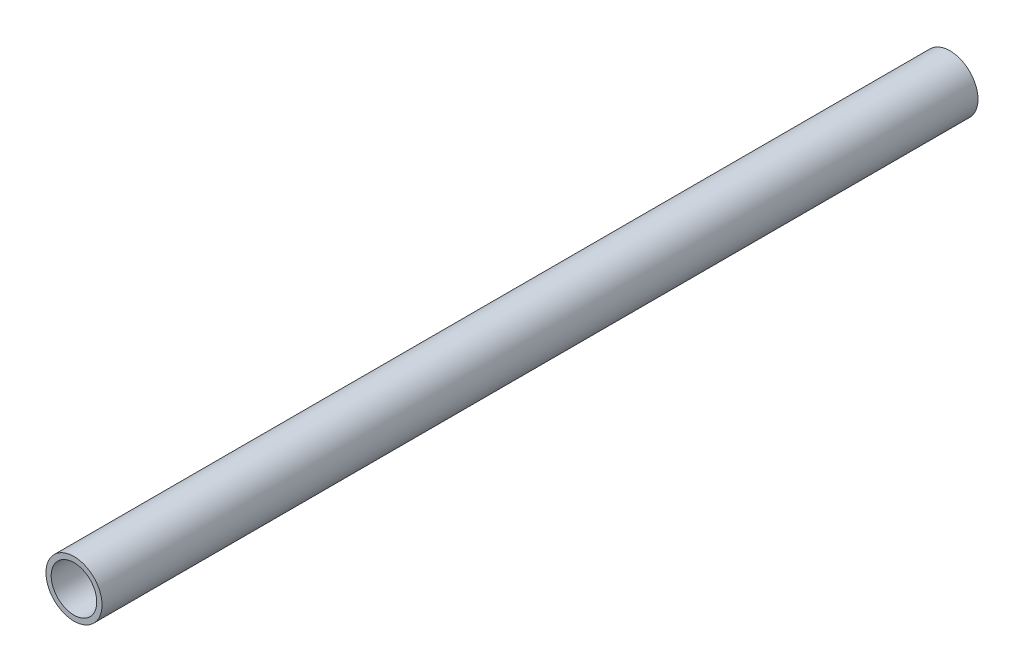
SolidWorks part; units mm, degrees
ref_plane "Alzado" through (0, 0, 0) normal (0, 0, 1) x (1, 0, 0)
ref_plane "Planta" through (0, 0, 0) normal (0, 1, 0) x (1, 0, 0)
ref_plane "Vista lateral" through (0, 0, 0) normal (1, 0, 0) x (0, 0, -1)
sketch "Croquis1" plane through (0, 0, 0) normal (0, 0, 1) x (1, 0, 0)
  circle A0 centre (0, 0) radius 16
  dimension "D1" = 32
extrude "Extruir1" add sketch "Croquis1" along normal mid plane 500
shell "Vaciado1" thickness 3
